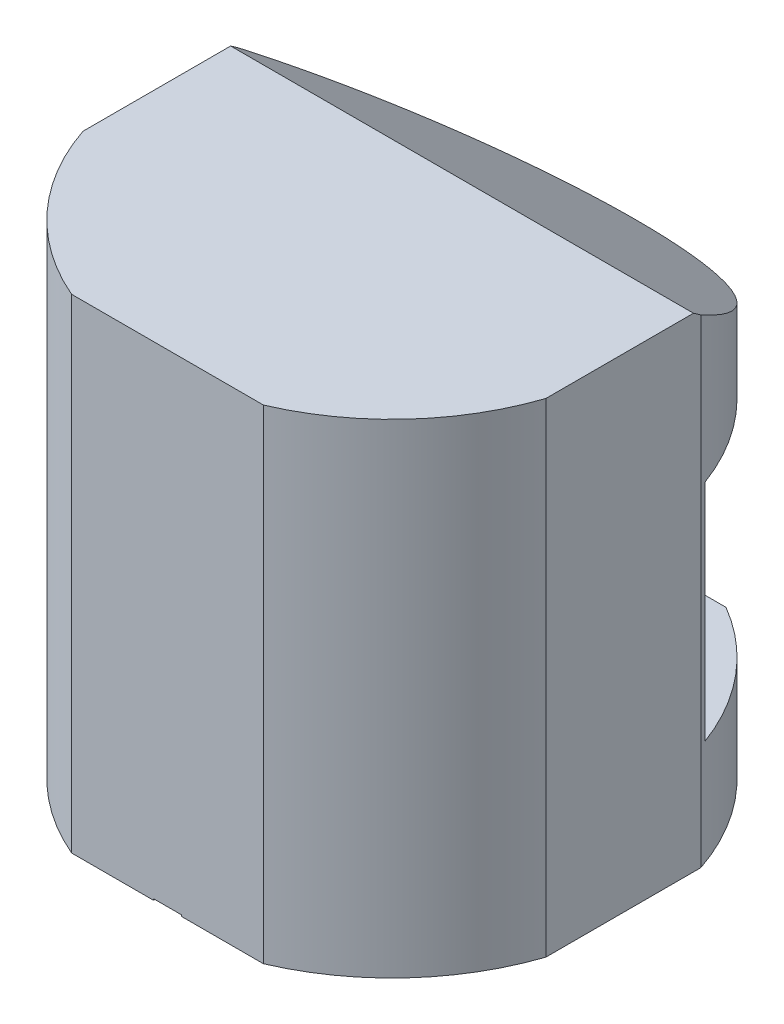
SolidWorks part; units mm, degrees
ref_plane "Front" through (0, 0, 0) normal (0, 0, 1) x (1, 0, 0)
ref_plane "Top" through (0, 0, 0) normal (0, 1, 0) x (1, 0, 0)
ref_plane "Right" through (0, 0, 0) normal (1, 0, 0) x (0, 0, -1)
sketch "Esquisse1" plane through (0, 0, 0) normal (0, 1, 0) x (1, 0, 0)
  line L1 (-165, -55.2359) -> (165, -55.2359) construction
  line L2 (-165, -55.2359) -> (-165, 55.2359)
  line L3 (-165, 55.2359) -> (165, 55.2359) construction
  line L4 (165, -55.2359) -> (165, 55.2359)
  line L5 (-165, -55.2359) -> (165, 55.2359) construction
  line L6 (-165, 55.2359) -> (165, -55.2359) construction
  line L9 (-68.3813, -160) -> (68.3813, -160)
  arc A0 (-165, -55.2359) -> (-68.3813, -160) centre (0, 0) ccw
  arc A2 (165, 55.2359) -> (-165, 55.2359) centre (0, 0) ccw
  arc A3 (68.3813, -160) -> (165, -55.2359) centre (0, 0) ccw
  point P0 (0, 0)
  dimension "D1" = 330
  dimension "D9" = 348
  dimension "D3" = 160
extrude "Boss.-Extru.1" add sketch "Esquisse1" along normal blind 345
sketch "Esquisse3" plane through (0, 0, 0) normal (-1, 0, 0) x (0, 0, 1)
  line L0 (-50, 345) -> (-542.7111, 0)
  line L1 (-55.2359, 345) -> (55.2359, 345) construction
  line L2 (-55.2359, 0) -> (55.2359, 0) construction
  line L3 (-542.7111, 0) -> (-542.7111, 345)
  line L4 (-55.2359, 0) -> (55.2359, 0) construction
  line L5 (-542.7111, 345) -> (-50, 345)
  line L6 (-60, 150) -> (-130, 150)
  line L7 (-174, 0) -> (-150, 0)
  line L8 (-174, 0) -> (-174, 235)
  line L9 (-174, 235) -> (-60, 235)
  line L10 (-150, 0) -> (-150, 75)
  line L11 (-60, 150) -> (-60, 235)
  line L14 (-174, 0) -> (-55.2359, 0) construction
  line L17 (-150, 75) -> (-130, 75)
  line L18 (-130, 150) -> (-130, 75)
  dimension "D1" = 35
  dimension "D2" = 50
  dimension "D3" = 235
  dimension "D4" = 150
  dimension "D5" = 60
  dimension "D6" = 150
  dimension "D7" = 75
  dimension "D8" = 130
extrude "Enlèv. mat.-Extru.1" cut sketch "Esquisse3" against normal through all both and the other way through all
sketch "Esquisse5" plane through (0, 150, 0) normal (0, 1, 0) x (1, 0, 0)
  line L1 (163.3279, 60) -> (-163.3279, 60) construction
  line L2 (-200, 60) -> (200, 60)
  line L3 (-200, 60) -> (-200, 130)
  line L4 (-200, 130) -> (200, 130)
  line L5 (200, 60) -> (200, 130)
  line L6 (115.6547, 130) -> (-115.6547, 130) construction
  point P0 (0, 60)
  dimension "D1" = 400
extrude "Enlèv. mat.-Extru.3" cut sketch "Esquisse5" against normal up to surface (75 mm away) up to face at (0, 75, -140.3361)
sketch "Esquisse6" plane through (0, 0, 0) normal (0, -1, 0) x (1, 0, 0)
  line L0 (-68.3813, 160) -> (68.3813, 160) construction
  line L1 (-10, 160) -> (10, 160)
  line L2 (-10, 160) -> (-10, 139)
  line L3 (-10, 139) -> (10, 139)
  line L4 (10, 160) -> (10, 139)
  point P4 (0, 139)
  dimension "D1" = 21
  dimension "D2" = 20
extrude "Enlèv. mat.-Extru.4" cut sketch "Esquisse6" against normal blind 1
